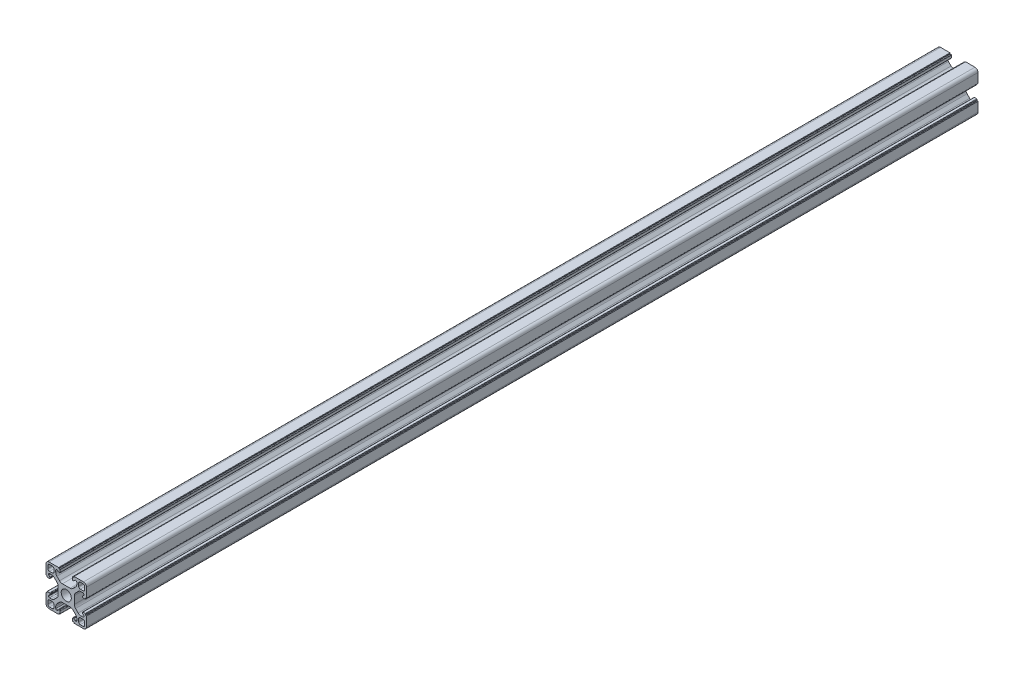
SolidWorks part; units mm, degrees
material "1060 Сплав"
ref_plane "Спереди" through (0, 0, 0) normal (0, 0, 1) x (1, 0, 0)
ref_plane "Сверху" through (0, 0, 0) normal (0, 1, 0) x (1, 0, 0)
ref_plane "Справа" through (0, 0, 0) normal (1, 0, 0) x (0, 0, -1)
sketch "Эскиз1" plane through (0, 0, 0) normal (0, 0, 1) x (1, 0, 0)
  line L0 (-22.0052, 70.3096) -> (-25.0052, 67.3096) construction
  line L1 (-31.1052, 65.2096) -> (-29.2064, 65.2096)
  line L2 (-31.1052, 61.2096) -> (-21.1052, 71.2096) construction
  line L3 (-23.5052, 68.8096) -> (-25.0052, 70.3096) construction
  line L4 (-27.7922, 65.7954) -> (-26.4909, 67.0967)
  line L5 (-24.2052, 67.3096) -> (-22.8052, 67.3096)
  line L6 (-25.0052, 68.1096) -> (-25.0052, 69.5096)
  line L7 (-22.8052, 70.3096) -> (-24.2052, 70.3096)
  line L8 (-25.9052, 69.4096) -> (-25.9052, 68.5109)
  line L9 (-27.3419, 69.2829) -> (-26.8616, 69.7632)
  line L10 (-27.9052, 70.7587) -> (-27.4052, 70.7587)
  line L11 (-27.5187, 69.2096) -> (-27.8052, 69.2096)
  line L12 (-26.508, 69.9096) -> (-26.4052, 69.9096)
  line L13 (-27.4052, 71.0596) -> (-27.4052, 70.7587)
  line L14 (-28.0552, 70.6087) -> (-28.0552, 69.4596)
  line L15 (-22.6052, 71.2096) -> (-27.2552, 71.2096)
  line L16 (-22.0052, 69.5096) -> (-22.0052, 68.1096)
  line L17 (-21.1052, 69.7096) -> (-21.1052, 65.0596)
  line L18 (-21.7061, 64.2596) -> (-22.8552, 64.2596)
  line L19 (-21.2552, 64.9096) -> (-21.5561, 64.9096)
  line L20 (-22.4052, 65.8068) -> (-22.4052, 65.9096)
  line L21 (-23.1052, 64.7961) -> (-23.1052, 64.5096)
  line L22 (-21.5561, 64.4096) -> (-21.5561, 64.9096)
  line L23 (-23.0319, 64.9729) -> (-22.5516, 65.4532)
  line L24 (-22.9052, 66.4096) -> (-23.8039, 66.4096)
  line L25 (-26.5194, 64.5226) -> (-25.2181, 65.8239)
  line L26 (-27.1052, 61.2096) -> (-27.1052, 63.1084)
  line L27 (-27.1052, 61.2096) -> (-27.1052, 59.3109)
  line L28 (-26.5194, 57.8967) -> (-25.2181, 56.5954)
  line L29 (-25.0052, 54.3096) -> (-25.0052, 52.9096)
  line L30 (-24.2052, 55.1096) -> (-22.8052, 55.1096)
  line L31 (-22.0052, 52.9096) -> (-22.0052, 54.3096)
  line L32 (-22.9052, 56.0096) -> (-23.8039, 56.0096)
  line L33 (-23.0319, 57.4464) -> (-22.5516, 56.9661)
  line L34 (-21.5561, 58.0096) -> (-21.5561, 57.5096)
  line L35 (-23.1052, 57.6232) -> (-23.1052, 57.9096)
  line L36 (-22.4052, 56.6125) -> (-22.4052, 56.5096)
  line L37 (-21.2552, 57.5096) -> (-21.5561, 57.5096)
  line L38 (-21.7061, 58.1596) -> (-22.8552, 58.1596)
  line L39 (-21.1052, 52.7096) -> (-21.1052, 57.3596)
  line L40 (-22.8052, 52.1096) -> (-24.2052, 52.1096)
  line L41 (-22.6052, 51.2096) -> (-27.2552, 51.2096)
  line L42 (-28.0552, 51.8106) -> (-28.0552, 52.9596)
  line L43 (-27.4052, 51.3596) -> (-27.4052, 51.6606)
  line L44 (-26.508, 52.5096) -> (-26.4052, 52.5096)
  line L45 (-27.5187, 53.2096) -> (-27.8052, 53.2096)
  line L46 (-27.9052, 51.6606) -> (-27.4052, 51.6606)
  line L47 (-27.3419, 53.1364) -> (-26.8616, 52.6561)
  line L48 (-25.9052, 53.0096) -> (-25.9052, 53.9084)
  line L49 (-27.7922, 56.6239) -> (-26.4909, 55.3226)
  line L50 (-31.1052, 57.2096) -> (-29.2064, 57.2096)
  line L51 (-22.0052, 52.1096) -> (-25.0052, 55.1096) construction
  line L52 (-31.1052, 61.2096) -> (-21.1052, 51.2096) construction
  line L53 (-23.5052, 53.6096) -> (-22.0052, 55.1096) construction
  line L54 (-31.1052, 57.2096) -> (-33.0039, 57.2096)
  line L55 (-34.4181, 56.6239) -> (-35.7194, 55.3226)
  line L56 (-38.0052, 55.1096) -> (-39.4052, 55.1096)
  line L57 (-37.2052, 54.3096) -> (-37.2052, 52.9096)
  line L58 (-39.4052, 52.1096) -> (-38.0052, 52.1096)
  line L59 (-36.3052, 53.0096) -> (-36.3052, 53.9084)
  line L60 (-34.8684, 53.1364) -> (-35.3487, 52.6561)
  line L61 (-34.3052, 51.6606) -> (-34.8052, 51.6606)
  line L62 (-34.6916, 53.2096) -> (-34.4052, 53.2096)
  line L63 (-35.7023, 52.5096) -> (-35.8052, 52.5096)
  line L64 (-34.8052, 51.3596) -> (-34.8052, 51.6606)
  line L65 (-34.1552, 51.8106) -> (-34.1552, 52.9596)
  line L66 (-39.6052, 51.2096) -> (-34.9552, 51.2096)
  line L67 (-40.2052, 52.9096) -> (-40.2052, 54.3096)
  line L68 (-41.1052, 52.7096) -> (-41.1052, 57.3596)
  line L69 (-40.5042, 58.1596) -> (-39.3552, 58.1596)
  line L70 (-40.9552, 57.5096) -> (-40.6542, 57.5096)
  line L71 (-39.8052, 56.6125) -> (-39.8052, 56.5096)
  line L72 (-39.1052, 57.6232) -> (-39.1052, 57.9096)
  line L73 (-40.6542, 58.0096) -> (-40.6542, 57.5096)
  line L74 (-39.1784, 57.4464) -> (-39.6587, 56.9661)
  line L75 (-39.3052, 56.0096) -> (-38.4064, 56.0096)
  line L76 (-35.6909, 57.8967) -> (-36.9922, 56.5954)
  line L77 (-35.1052, 61.2096) -> (-35.1052, 59.3109)
  line L78 (-40.2052, 52.1096) -> (-37.2052, 55.1096) construction
  line L79 (-31.1052, 61.2096) -> (-41.1052, 51.2096) construction
  line L80 (-38.7052, 53.6096) -> (-37.2052, 52.1096) construction
  line L81 (-35.1052, 61.2096) -> (-35.1052, 63.1084)
  line L82 (-35.6909, 64.5226) -> (-36.9922, 65.8239)
  line L83 (-37.2052, 68.1096) -> (-37.2052, 69.5096)
  line L84 (-38.0052, 67.3096) -> (-39.4052, 67.3096)
  line L85 (-40.2052, 69.5096) -> (-40.2052, 68.1096)
  line L86 (-39.3052, 66.4096) -> (-38.4064, 66.4096)
  line L87 (-39.1784, 64.9729) -> (-39.6587, 65.4532)
  line L88 (-40.6542, 64.4096) -> (-40.6542, 64.9096)
  line L89 (-39.1052, 64.7961) -> (-39.1052, 64.5096)
  line L90 (-39.8052, 65.8068) -> (-39.8052, 65.9096)
  line L91 (-40.9552, 64.9096) -> (-40.6542, 64.9096)
  line L92 (-40.5042, 64.2596) -> (-39.3552, 64.2596)
  line L93 (-41.1052, 69.7096) -> (-41.1052, 65.0596)
  line L94 (-39.4052, 70.3096) -> (-38.0052, 70.3096)
  line L95 (-39.6052, 71.2096) -> (-34.9552, 71.2096)
  line L96 (-34.1552, 70.6087) -> (-34.1552, 69.4596)
  line L97 (-34.8052, 71.0596) -> (-34.8052, 70.7587)
  line L98 (-35.7023, 69.9096) -> (-35.8052, 69.9096)
  line L99 (-34.6916, 69.2096) -> (-34.4052, 69.2096)
  line L100 (-34.3052, 70.7587) -> (-34.8052, 70.7587)
  line L101 (-34.8684, 69.2829) -> (-35.3487, 69.7632)
  line L102 (-36.3052, 69.4096) -> (-36.3052, 68.5109)
  line L103 (-34.4181, 65.7954) -> (-35.7194, 67.0967)
  line L104 (-31.1052, 65.2096) -> (-33.0039, 65.2096)
  line L105 (-42.8692, 61.2096) -> (-19.6008, 61.2096) construction
  line L106 (-40.2052, 70.3096) -> (-37.2052, 67.3096) construction
  line L107 (-31.1052, 49.1232) -> (-31.1052, 71.9286) construction
  line L108 (-31.1052, 61.2096) -> (-41.1052, 71.2096) construction
  line L109 (-38.7052, 68.8096) -> (-40.2052, 67.3096) construction
  arc A0 (-22.0052, 69.5096) -> (-22.8052, 70.3096) centre (-22.8052, 69.5096) ccw
  arc A1 (-24.2052, 70.3096) -> (-25.0052, 69.5096) centre (-24.2052, 69.5096) ccw
  arc A2 (-24.2052, 67.3096) -> (-25.0052, 68.1096) centre (-24.2052, 68.1096) cw
  arc A3 (-22.6052, 71.2096) -> (-21.1052, 69.7096) centre (-22.6052, 69.7096) cw
  arc A4 (-27.9052, 70.7587) -> (-28.0552, 70.6087) centre (-27.9052, 70.6087) ccw
  arc A5 (-27.2552, 71.2096) -> (-27.4052, 71.0596) centre (-27.2552, 71.0596) ccw
  arc A6 (-27.5187, 69.2096) -> (-27.3419, 69.2829) centre (-27.5187, 69.4596) ccw
  arc A7 (-27.8052, 69.2096) -> (-28.0552, 69.4596) centre (-27.8052, 69.4596) cw
  arc A8 (-26.8616, 69.7632) -> (-26.508, 69.9096) centre (-26.508, 69.4096) cw
  arc A9 (-26.4052, 69.9096) -> (-25.9052, 69.4096) centre (-26.4052, 69.4096) cw
  arc A10 (-28.6052, 61.2096) -> (-31.1052, 63.7096) centre (-31.1052, 61.2096) ccw
  arc A11 (-29.2064, 65.2096) -> (-27.7922, 65.7954) centre (-29.2064, 67.2096) ccw
  arc A12 (-25.9052, 68.5109) -> (-26.4909, 67.0967) centre (-27.9052, 68.5109) cw
  arc A13 (-22.0052, 68.1096) -> (-22.8052, 67.3096) centre (-22.8052, 68.1096) cw
  arc A14 (-22.4052, 65.9096) -> (-22.9052, 66.4096) centre (-22.9052, 65.9096) ccw
  arc A15 (-22.5516, 65.4532) -> (-22.4052, 65.8068) centre (-22.9052, 65.8068) ccw
  arc A16 (-23.1052, 64.5096) -> (-22.8552, 64.2596) centre (-22.8552, 64.5096) ccw
  arc A17 (-23.1052, 64.7961) -> (-23.0319, 64.9729) centre (-22.8552, 64.7961) cw
  arc A18 (-21.1052, 65.0596) -> (-21.2552, 64.9096) centre (-21.2552, 65.0596) cw
  arc A19 (-21.5561, 64.4096) -> (-21.7061, 64.2596) centre (-21.7061, 64.4096) cw
  arc A20 (-23.8039, 66.4096) -> (-25.2181, 65.8239) centre (-23.8039, 64.4096) ccw
  arc A21 (-27.1052, 63.1084) -> (-26.5194, 64.5226) centre (-25.1052, 63.1084) cw
  arc A22 (-22.8052, 52.1096) -> (-22.0052, 52.9096) centre (-22.8052, 52.9096) ccw
  arc A23 (-22.0052, 54.3096) -> (-22.8052, 55.1096) centre (-22.8052, 54.3096) ccw
  arc A24 (-25.0052, 54.3096) -> (-24.2052, 55.1096) centre (-24.2052, 54.3096) cw
  arc A25 (-21.1052, 52.7096) -> (-22.6052, 51.2096) centre (-22.6052, 52.7096) cw
  arc A26 (-21.5561, 58.0096) -> (-21.7061, 58.1596) centre (-21.7061, 58.0096) ccw
  arc A27 (-21.1052, 57.3596) -> (-21.2552, 57.5096) centre (-21.2552, 57.3596) ccw
  arc A28 (-23.1052, 57.6232) -> (-23.0319, 57.4464) centre (-22.8552, 57.6232) ccw
  arc A29 (-23.1052, 57.9096) -> (-22.8552, 58.1596) centre (-22.8552, 57.9096) cw
  arc A30 (-22.5516, 56.9661) -> (-22.4052, 56.6125) centre (-22.9052, 56.6125) cw
  arc A31 (-22.4052, 56.5096) -> (-22.9052, 56.0096) centre (-22.9052, 56.5096) cw
  arc A32 (-31.1052, 58.7096) -> (-28.6052, 61.2096) centre (-31.1052, 61.2096) ccw
  arc A33 (-27.1052, 59.3109) -> (-26.5194, 57.8967) centre (-25.1052, 59.3109) ccw
  arc A34 (-23.8039, 56.0096) -> (-25.2181, 56.5954) centre (-23.8039, 58.0096) cw
  arc A35 (-24.2052, 52.1096) -> (-25.0052, 52.9096) centre (-24.2052, 52.9096) cw
  arc A36 (-26.4052, 52.5096) -> (-25.9052, 53.0096) centre (-26.4052, 53.0096) ccw
  arc A37 (-26.8616, 52.6561) -> (-26.508, 52.5096) centre (-26.508, 53.0096) ccw
  arc A38 (-27.8052, 53.2096) -> (-28.0552, 52.9596) centre (-27.8052, 52.9596) ccw
  arc A39 (-27.5187, 53.2096) -> (-27.3419, 53.1364) centre (-27.5187, 52.9596) cw
  arc A40 (-27.2552, 51.2096) -> (-27.4052, 51.3596) centre (-27.2552, 51.3596) cw
  arc A41 (-27.9052, 51.6606) -> (-28.0552, 51.8106) centre (-27.9052, 51.8106) cw
  arc A42 (-25.9052, 53.9084) -> (-26.4909, 55.3226) centre (-27.9052, 53.9084) ccw
  arc A43 (-29.2064, 57.2096) -> (-27.7922, 56.6239) centre (-29.2064, 55.2096) cw
  arc A44 (-40.2052, 52.9096) -> (-39.4052, 52.1096) centre (-39.4052, 52.9096) ccw
  arc A45 (-38.0052, 52.1096) -> (-37.2052, 52.9096) centre (-38.0052, 52.9096) ccw
  arc A46 (-38.0052, 55.1096) -> (-37.2052, 54.3096) centre (-38.0052, 54.3096) cw
  arc A47 (-39.6052, 51.2096) -> (-41.1052, 52.7096) centre (-39.6052, 52.7096) cw
  arc A48 (-34.3052, 51.6606) -> (-34.1552, 51.8106) centre (-34.3052, 51.8106) ccw
  arc A49 (-34.9552, 51.2096) -> (-34.8052, 51.3596) centre (-34.9552, 51.3596) ccw
  arc A50 (-34.6916, 53.2096) -> (-34.8684, 53.1364) centre (-34.6916, 52.9596) ccw
  arc A51 (-34.4052, 53.2096) -> (-34.1552, 52.9596) centre (-34.4052, 52.9596) cw
  arc A52 (-35.3487, 52.6561) -> (-35.7023, 52.5096) centre (-35.7023, 53.0096) cw
  arc A53 (-35.8052, 52.5096) -> (-36.3052, 53.0096) centre (-35.8052, 53.0096) cw
  arc A54 (-33.6052, 61.2096) -> (-31.1052, 58.7096) centre (-31.1052, 61.2096) ccw
  arc A55 (-33.0039, 57.2096) -> (-34.4181, 56.6239) centre (-33.0039, 55.2096) ccw
  arc A56 (-36.3052, 53.9084) -> (-35.7194, 55.3226) centre (-34.3052, 53.9084) cw
  arc A57 (-40.2052, 54.3096) -> (-39.4052, 55.1096) centre (-39.4052, 54.3096) cw
  arc A58 (-39.8052, 56.5096) -> (-39.3052, 56.0096) centre (-39.3052, 56.5096) ccw
  arc A59 (-39.6587, 56.9661) -> (-39.8052, 56.6125) centre (-39.3052, 56.6125) ccw
  arc A60 (-39.1052, 57.9096) -> (-39.3552, 58.1596) centre (-39.3552, 57.9096) ccw
  arc A61 (-39.1052, 57.6232) -> (-39.1784, 57.4464) centre (-39.3552, 57.6232) cw
  arc A62 (-41.1052, 57.3596) -> (-40.9552, 57.5096) centre (-40.9552, 57.3596) cw
  arc A63 (-40.6542, 58.0096) -> (-40.5042, 58.1596) centre (-40.5042, 58.0096) cw
  arc A64 (-38.4064, 56.0096) -> (-36.9922, 56.5954) centre (-38.4064, 58.0096) ccw
  arc A65 (-35.1052, 59.3109) -> (-35.6909, 57.8967) centre (-37.1052, 59.3109) cw
  arc A66 (-39.4052, 70.3096) -> (-40.2052, 69.5096) centre (-39.4052, 69.5096) ccw
  arc A67 (-40.2052, 68.1096) -> (-39.4052, 67.3096) centre (-39.4052, 68.1096) ccw
  arc A68 (-37.2052, 68.1096) -> (-38.0052, 67.3096) centre (-38.0052, 68.1096) cw
  arc A69 (-41.1052, 69.7096) -> (-39.6052, 71.2096) centre (-39.6052, 69.7096) cw
  arc A70 (-40.6542, 64.4096) -> (-40.5042, 64.2596) centre (-40.5042, 64.4096) ccw
  arc A71 (-41.1052, 65.0596) -> (-40.9552, 64.9096) centre (-40.9552, 65.0596) ccw
  arc A72 (-39.1052, 64.7961) -> (-39.1784, 64.9729) centre (-39.3552, 64.7961) ccw
  arc A73 (-39.1052, 64.5096) -> (-39.3552, 64.2596) centre (-39.3552, 64.5096) cw
  arc A74 (-39.6587, 65.4532) -> (-39.8052, 65.8068) centre (-39.3052, 65.8068) cw
  arc A75 (-39.8052, 65.9096) -> (-39.3052, 66.4096) centre (-39.3052, 65.9096) cw
  arc A76 (-31.1052, 63.7096) -> (-33.6052, 61.2096) centre (-31.1052, 61.2096) ccw
  arc A77 (-35.1052, 63.1084) -> (-35.6909, 64.5226) centre (-37.1052, 63.1084) ccw
  arc A78 (-38.4064, 66.4096) -> (-36.9922, 65.8239) centre (-38.4064, 64.4096) cw
  arc A79 (-38.0052, 70.3096) -> (-37.2052, 69.5096) centre (-38.0052, 69.5096) cw
  arc A80 (-35.8052, 69.9096) -> (-36.3052, 69.4096) centre (-35.8052, 69.4096) ccw
  arc A81 (-35.3487, 69.7632) -> (-35.7023, 69.9096) centre (-35.7023, 69.4096) ccw
  arc A82 (-34.4052, 69.2096) -> (-34.1552, 69.4596) centre (-34.4052, 69.4596) ccw
  arc A83 (-34.6916, 69.2096) -> (-34.8684, 69.2829) centre (-34.6916, 69.4596) cw
  arc A84 (-34.9552, 71.2096) -> (-34.8052, 71.0596) centre (-34.9552, 71.0596) cw
  arc A85 (-34.3052, 70.7587) -> (-34.1552, 70.6087) centre (-34.3052, 70.6087) cw
  arc A86 (-36.3052, 68.5109) -> (-35.7194, 67.0967) centre (-34.3052, 68.5109) ccw
  arc A87 (-33.0039, 65.2096) -> (-34.4181, 65.7954) centre (-33.0039, 67.2096) cw
  point P0 (-31.1052, 61.2096)
  point P9 (-31.1052, 61.2096)
  point P40 (-22.4052, 64.9096)
  point P93 (-27.4052, 52.5096)
  point P144 (-27.4052, 69.9096)
  point P152 (-22.4052, 57.5096)
  point P153 (-31.1052, 57.2854)
  point P154 (-31.1052, 61.2096)
  point P189 (-39.8052, 57.5096)
  point P228 (-34.8052, 52.5096)
  point P229 (-35.0294, 61.2096)
  point P230 (-31.1052, 61.2096)
  point P268 (-34.8052, 69.9096)
  point P273 (-27.1809, 61.2096)
  point P306 (-39.8052, 64.9096)
  point P307 (-31.1052, 65.1339)
  point P309 (-31.1052, 61.2096)
  dimension "D3" = 5
  dimension "D6" = 2
  dimension "D1" = 2
  dimension "D2" = 6
  dimension "D4" = 4
  dimension "D5" = 0.9
extrude "Бобышка-Вытянуть1" add sketch "Эскиз1" along normal blind 440
